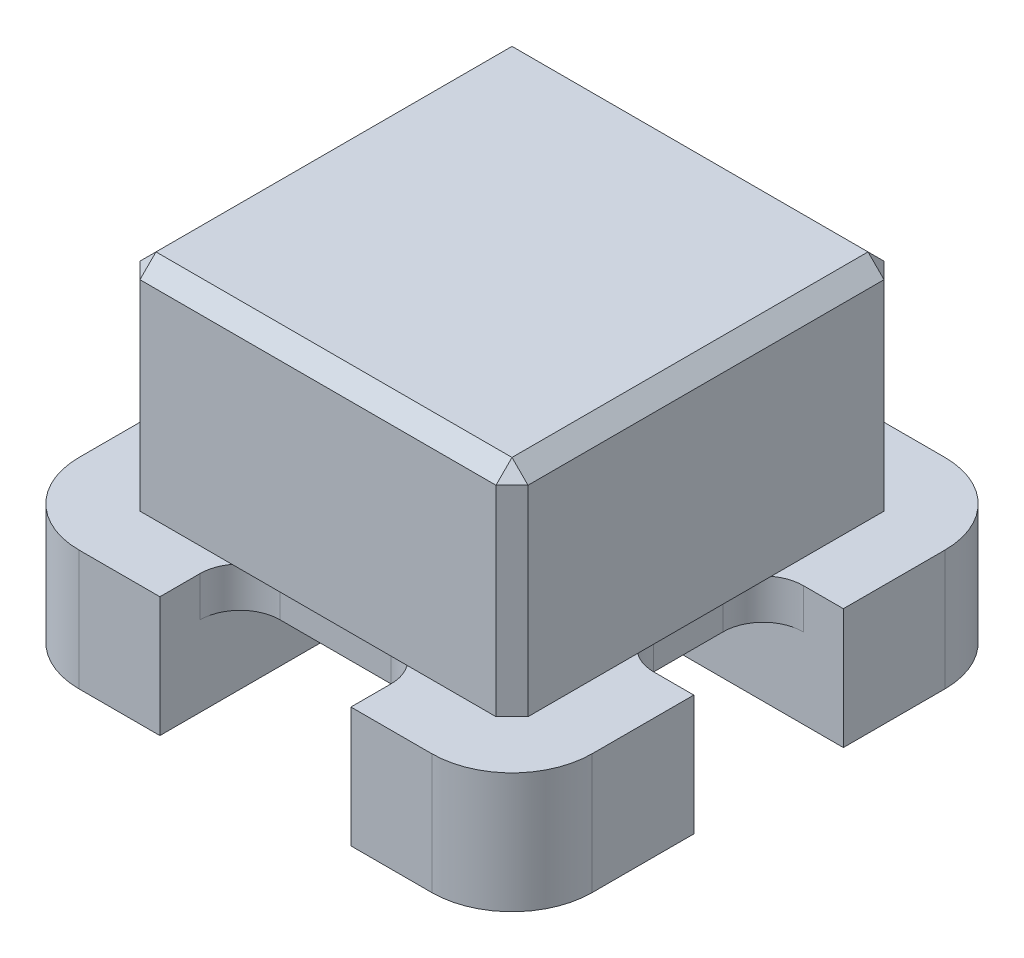
SolidWorks part; units mm, degrees
other "top"
other "bottom"
ref_plane "Front Plane" through (0, 0, 0) normal (0, 0, 1) x (1, 0, 0)
ref_plane "Top Plane" through (0, 0, 0) normal (0, 1, 0) x (1, 0, 0)
ref_plane "Right Plane" through (0, 0, 0) normal (1, 0, 0) x (0, 0, -1)
sketch "Sketch1" plane through (0, 0, 0) normal (0, 1, 0) x (1, 0, 0)
  line L1 (-20, -20) -> (20, -20)
  line L2 (-20, -20) -> (-20, 20)
  line L3 (-20, 20) -> (20, 20)
  line L4 (20, -20) -> (20, 20)
  line L5 (-20, -20) -> (20, 20) construction
  line L6 (-20, 20) -> (20, -20) construction
  point P0 (0, 0)
  dimension "D1" = 40
extrude "Extrude-Thin1" add sketch "Sketch1" along normal blind 30 thin
sketch "Sketch3" plane through (0, 0, 0) normal (0, -1, 0) x (1, 0, 0)
  line L0 (-20, -20) -> (-20, 20) construction
  line L1 (-20, 0) -> (27.9302, 0) construction
  line L2 (0, 0) -> (0, 25.4647) construction
  line L3 (-20, 20) -> (20, 20) construction
  line L4 (-20, 20) -> (20, 20)
  line L5 (-20, -20) -> (-20, 20)
  line L6 (20, -20) -> (-20, -20) construction
  line L7 (20, -20) -> (-20, -20)
  line L8 (20, 20) -> (20, -20) construction
  line L9 (20, 20) -> (20, -20)
  circle A1 centre (-20, 0) radius 7.0233
  circle A6 centre (20, 0) radius 7.0233
  circle A7 centre (0, 0) radius 7.0233
extrude "Boss-Extrude1" add sketch "Sketch3" against normal blind 2
sketch "Sketch4" plane through (0, 0, 0) normal (0, -1, 0) x (1, 0, 0)
  line L5 (0, 0) -> (27.6547, 0) construction
  line L13 (32, -32) -> (32, 32)
  line L14 (32, 32) -> (-32, 32)
  line L15 (-32, 32) -> (-32, -32)
  line L16 (-32, -32) -> (32, -32)
  line L17 (22, -22) -> (22, 22)
  line L18 (22, 22) -> (-22, 22)
  line L19 (-22, 22) -> (-22, -22)
  line L20 (-22, -22) -> (22, -22)
  line L21 (22, -22) -> (22, 22)
  line L22 (22, 22) -> (-22, 22)
  line L23 (-22, 22) -> (-22, -22)
  line L24 (-22, -22) -> (22, -22)
  line L26 (-11.9116, -45.2978) -> (11.9116, -45.2978)
  line L27 (-11.9116, -45.2978) -> (-11.9116, 45.2978)
  line L28 (-11.9116, 45.2978) -> (11.9116, 45.2978)
  line L29 (11.9116, -45.2978) -> (11.9116, 45.2978)
  line L30 (-11.9116, -45.2978) -> (11.9116, 45.2978) construction
  line L31 (-11.9116, 45.2978) -> (11.9116, -45.2978) construction
  line L32 (-50.2519, -9.326) -> (50.2519, -9.326)
  line L33 (-50.2519, -9.326) -> (-50.2519, 9.326)
  line L34 (-50.2519, 9.326) -> (50.2519, 9.326)
  line L35 (50.2519, -9.326) -> (50.2519, 9.326)
  line L36 (-50.2519, -9.326) -> (50.2519, 9.326) construction
  line L37 (-50.2519, 9.326) -> (50.2519, -9.326) construction
  line M5 (22, -22) -> (22, 22)
  line M6 (22, 22) -> (-22, 22)
  line M7 (-22, 22) -> (-22, -22)
  line M8 (-22, -22) -> (22, -22)
  dimension "D1" = 0
  dimension "D2" = 10
extrude "Boss-Extrude2" add sketch "Sketch4" along normal blind 15 from offset 5 contours L15 L34 L22 L27 L14 M7 | L34 L13 L14 L29 M5 M6 | L32 L29 L16 L13 M5 M8 | L32 L29 M8 M5 | L32 L15 L16 L27 L23 M8 | L32 L23 L27 M8 | L34 L27 L22 M7 | L29 L34 M5 M6 offset against normal yes
sketch "Sketch5" plane through (0, 30, 0) normal (0, 1, 0) x (1, 0, 0)
  line L8 (22.2, -22.2) -> (22.2, 22.2)
  line L9 (22.2, 22.2) -> (-22.2, 22.2)
  line L10 (-22.2, 22.2) -> (-22.2, -22.2)
  line L11 (-22.2, -22.2) -> (22.2, -22.2)
  line L12 (22.2, -22.2) -> (22.2, 22.2)
  line L13 (22.2, 22.2) -> (-22.2, 22.2)
  line L14 (-22.2, 22.2) -> (-22.2, -22.2)
  line L15 (-22.2, -22.2) -> (22.2, -22.2)
  dimension "D1" = 0.2
extrude "Extrude-Thin2" add sketch "Sketch5" against normal offset from surface (25 mm away) 0.2 from offset 0.2 thin
sketch "Sketch6" plane through (0, 30.2, 0) normal (0, 1, 0) x (1, 0, 0)
  line L4 (-24.2, -24.2) -> (24.2, -24.2)
  line L5 (24.2, -24.2) -> (24.2, 24.2)
  line L6 (24.2, 24.2) -> (-24.2, 24.2)
  line L7 (-24.2, 24.2) -> (-24.2, -24.2)
  line L8 (-24.2, -24.2) -> (24.2, -24.2)
  line L9 (24.2, -24.2) -> (24.2, 24.2)
  line L10 (24.2, 24.2) -> (-24.2, 24.2)
  line L11 (-24.2, 24.2) -> (-24.2, -24.2)
  dimension "D1" = 0
extrude "Boss-Extrude3" add sketch "Sketch6" along normal blind 2
chamfer "Chamfer2" distance 2 angle 45 8 edges at (-24.2, 18.7, -24.2) (24.2, 18.7, -24.2) (-24.2, 32.2, 0) (0, 32.2, 24.2) (24.2, 32.2, 0) (0, 32.2, -24.2) (24.2, 18.7, 24.2) (-24.2, 18.7, 24.2)
fillet "Fillet1" radius 10 4 edges at (-32, -2.5, 32) (32, -2.5, 32) (-32, -2.5, -32) (32, -2.5, -32)
fillet "Fillet2" radius 5 8 edges at (22, 2.5, 9.326) (22, 2.5, -9.326) (11.9116, 2.5, 22) (-11.9116, 2.5, 22) (-22, 2.5, -9.326) (-22, 2.5, 9.326) (-11.9116, 2.5, -22) (11.9116, 2.5, -22)
other "Save Bodies1"
